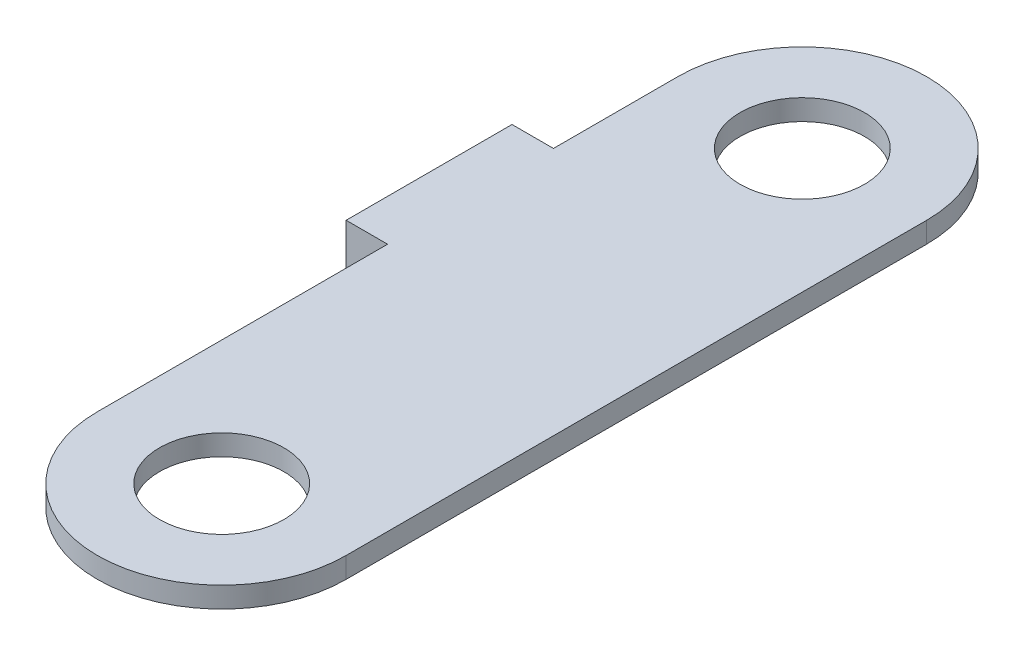
SolidWorks part; units mm, degrees
ref_plane "Front Plane" through (0, 0, 0) normal (0, 0, 1) x (1, 0, 0)
ref_plane "Top Plane" through (0, 0, 0) normal (0, 1, 0) x (1, 0, 0)
ref_plane "Right Plane" through (0, 0, 0) normal (1, 0, 0) x (0, 0, -1)
sketch "Sketch1" plane through (0, 0, 0) normal (0, 1, 0) x (1, 0, 0)
  line L0 (-38.1, 0) -> (-38.1, -177.8)
  line L1 (38.1, 0) -> (38.1, -177.8)
  arc A0 (38.1, 0) -> (-38.1, 0) centre (0, 0) ccw
  arc A1 (-38.1, -177.8) -> (38.1, -177.8) centre (0, -177.8) ccw
  circle A2 centre (0, 0) radius 19.05
  circle A3 centre (0, -177.8) radius 19.05
  dimension "D1" = 76.2
  dimension "D2" = 76.2
  dimension "D4" = 38.1
  dimension "D5" = 38.1
  dimension "D3" = 177.8
extrude "Boss-Extrude1" add sketch "Sketch1" along normal blind 6.35 contours A0 L0 A1 L1
sketch "Sketch2" plane through (0, 6.35, 0) normal (0, 1, 0) x (1, 0, 0)
  line L6 (-38.1, -88.9) -> (-50.8, -88.9)
  line L7 (-38.1, 0) -> (-38.1, -177.8) construction
  line L8 (-50.8, -88.9) -> (-50.8, -38.1)
  line L9 (-50.8, -38.1) -> (-38.1, -38.1)
  line L10 (-38.1, -38.1) -> (-38.1, -88.9)
  dimension "D3" = 50.8
  dimension "D4" = 12.7
extrude "Boss-Extrude4" add sketch "Sketch2" against normal blind 25.4
